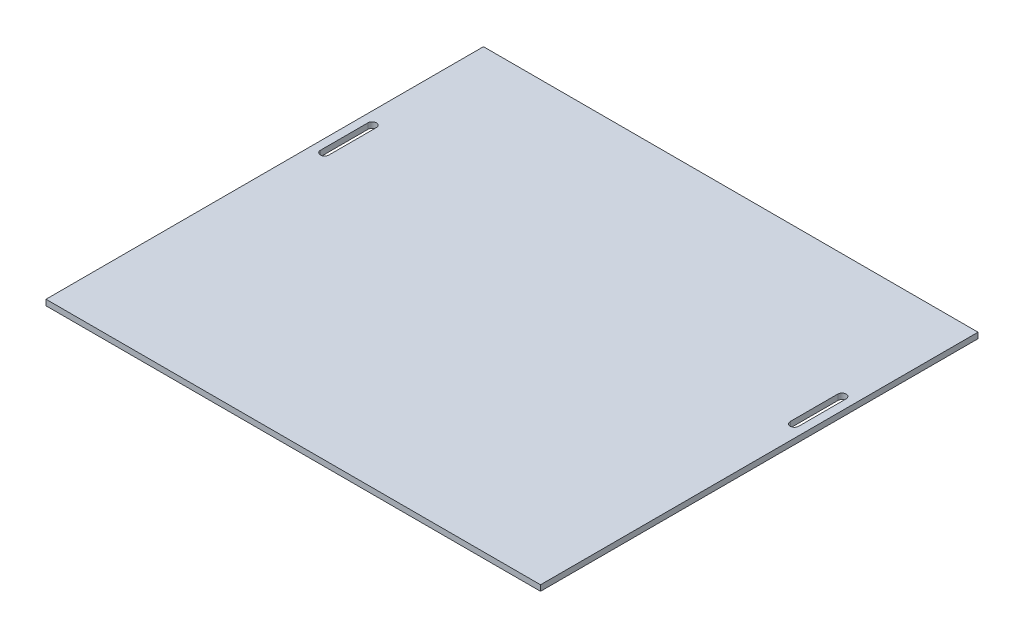
SolidWorks part; units mm, degrees
ref_plane "前视基准面" through (0, 0, 0) normal (0, 0, 1) x (1, 0, 0)
ref_plane "上视基准面" through (0, 0, 0) normal (0, 1, 0) x (1, 0, 0)
ref_plane "右视基准面" through (0, 0, 0) normal (1, 0, 0) x (0, 0, -1)
sketch "Sketch1" plane through (0, 0, 0) normal (0, 1, 0) x (1, 0, 0)
  line L0 (0, 0) -> (0, -230)
  line L1 (0, -230) -> (260, -230)
  line L2 (260, -230) -> (260, 0)
  line L3 (260, 0) -> (0, 0)
  dimension "D1" = 260
  dimension "D2" = 230
extrude "Boss-Extrude1" add sketch "Sketch1" along normal blind 3
sketch "Sketch2" plane through (0, 3, 0) normal (0, 1, 0) x (1, 0, 0)
  line L0 (0, 11.6263) -> (0, -241.004) construction
  line L1 (6.5, 11.6263) -> (6.5, -241.004) construction
  line L2 (-10, 0) -> (40, 0) construction
  line L3 (260, 0) -> (0, 0) construction
  line L5 (-10, -65) -> (40, -65) construction
  line L6 (-10, -90) -> (40, -90) construction
  line L7 (6.5, -65) -> (6.5, -90) construction
  line L8 (8.7, -65) -> (8.7, -90)
  line L9 (4.3, -65) -> (4.3, -90)
  line L10 (130, 8.235) -> (130, -26.4946) construction
  line L11 (253.5, -65) -> (253.5, -90) construction
  line L12 (251.3, -65) -> (251.3, -90)
  line L13 (255.7, -65) -> (255.7, -90)
  arc A0 (8.7, -65) -> (4.3, -65) centre (6.5, -65) ccw
  arc A1 (4.3, -90) -> (8.7, -90) centre (6.5, -90) ccw
  arc A2 (251.3, -65) -> (255.7, -65) centre (253.5, -65) cw
  arc A3 (255.7, -90) -> (251.3, -90) centre (253.5, -90) cw
  point P15 (6.5, -77.5)
  point P24 (253.5, -77.5)
  dimension "D6" = 2.2
  dimension "D2" = 10
  dimension "D3" = 50
  dimension "D7" = 25
  dimension "D8" = 130
  dimension "D1" = 6.5
  dimension "D4" = 65
  dimension "D5" = 90
extrude "Cut-Extrude1" cut sketch "Sketch2" against normal through all
